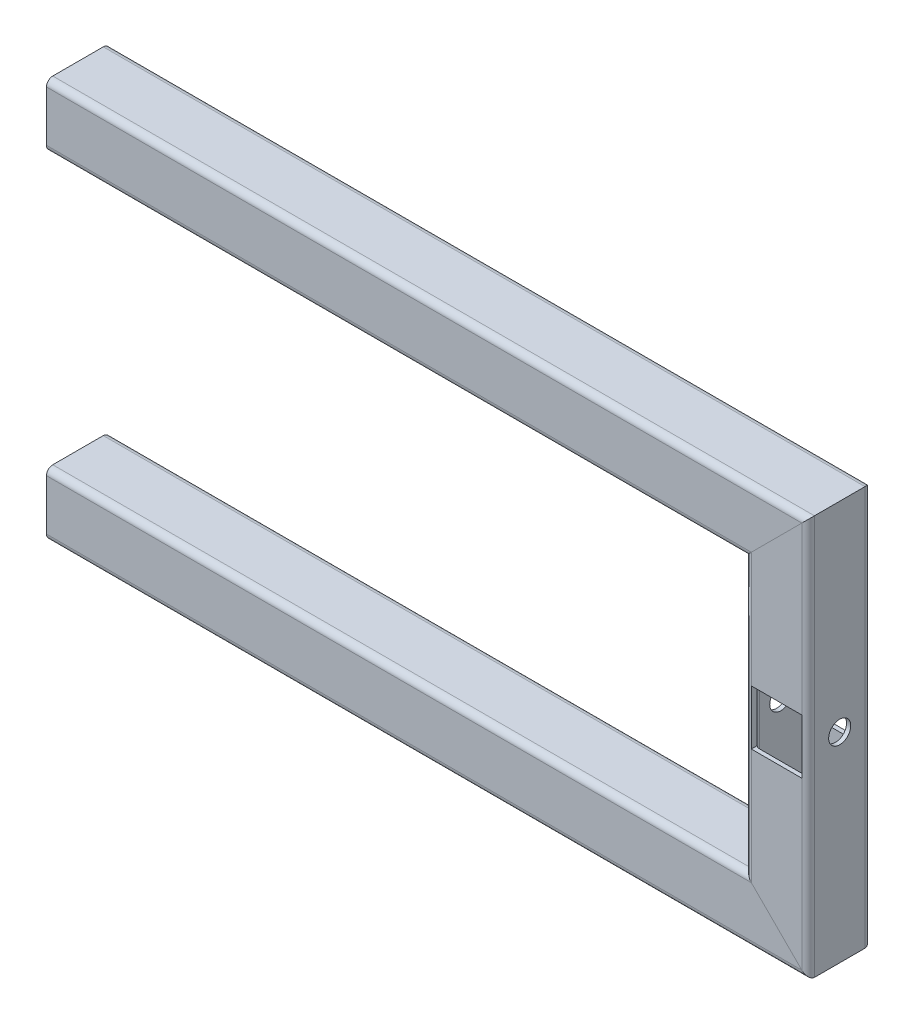
SolidWorks part; units mm, degrees
ref_plane "Plan de face" through (0, 0, 0) normal (0, 0, 1) x (1, 0, 0)
ref_plane "Plan de dessus" through (0, 0, 0) normal (0, 1, 0) x (1, 0, 0)
ref_plane "Plan de droite" through (0, 0, 0) normal (1, 0, 0) x (0, 0, -1)
sketch "Esquisse1" plane through (0, 0, 0) normal (0, 0, 1) x (1, 0, 0)
  line L0 (0, 0) -> (347, 0)
  line L1 (347, 0) -> (347, 160)
  line L2 (347, 160) -> (0, 160)
  dimension "D1" = 347
  dimension "D2" = 160
sketch "Esquisse2" plane through (0, 0, 0) normal (1, 0, 0) x (0, 0, -1)
  line L1 (-12, -15) -> (12, -15)
  line L2 (-15, -12) -> (-15, 12)
  line L3 (-12, 15) -> (12, 15)
  line L4 (15, -12) -> (15, 12)
  line L5 (0, 15) -> (0, -15) construction
  line L6 (-15, 0) -> (15, 0) construction
  line L7 (-10, -13) -> (10, -13)
  line L8 (-13, -10) -> (-13, 10)
  line L9 (-10, 13) -> (10, 13)
  line L10 (13, -10) -> (13, 10)
  line L11 (0, 13) -> (0, -13) construction
  line L12 (-13, 0) -> (13, 0) construction
  arc A0 (10, -13) -> (13, -10) centre (10, -10) ccw
  arc A1 (12, -15) -> (15, -12) centre (12, -12) ccw
  arc A2 (-13, 10) -> (-10, 13) centre (-10, 10) cw
  arc A3 (-10, -13) -> (-13, -10) centre (-10, -10) cw
  arc A4 (10, 13) -> (13, 10) centre (10, 10) cw
  arc A5 (-12, -15) -> (-15, -12) centre (-12, -12) cw
  arc A6 (12, 15) -> (15, 12) centre (12, 12) cw
  arc A7 (-15, 12) -> (-12, 15) centre (-12, 12) cw
  point P0 (0, 0)
  point P4 (0, 0)
  point P13 (13, -13)
  point P19 (15, -15)
  point P22 (-13, 13)
  point P27 (13, 13)
  point P32 (15, 15)
  point P35 (-15, 15)
  dimension "D5" = 3
  dimension "D1" = 30
  dimension "D2" = 30
  dimension "D3" = 26
  dimension "D4" = 26
sweep "Balayage1" add profiles "Esquisse2" path "Esquisse1"
sketch "Esquisse3" plane through (362, 0, 0) normal (1, 0, 0) x (0, 0, -1)
  line L3 (-12, -15) -> (-12, 175) construction
  circle A0 centre (0, 80) radius 5.25
  point P2 (0, 0)
  point P4 (0, 0)
  point P7 (-12, 80)
  dimension "D1" = 10.5
extrude "Enlèv. mat.-Extru.1" cut sketch "Esquisse3" against normal blind 46
sketch "Esquisse4" plane through (0, 0, 15) normal (0, 0, 1) x (1, 0, 0)
  line L0 (347, 0) -> (347, 160) construction
  line L1 (335, 67) -> (359, 67)
  line L2 (335, 67) -> (335, 93)
  line L3 (335, 93) -> (359, 93)
  line L4 (359, 67) -> (359, 93)
  line L5 (347, 93) -> (347, 67) construction
  line L6 (335, 80) -> (359, 80) construction
  line L7 (359, -12) -> (359, 172) construction
  point P0 (347, 80)
  dimension "D1" = 26
extrude "Enlèv. mat.-Extru.2" cut sketch "Esquisse4" against normal blind 46
